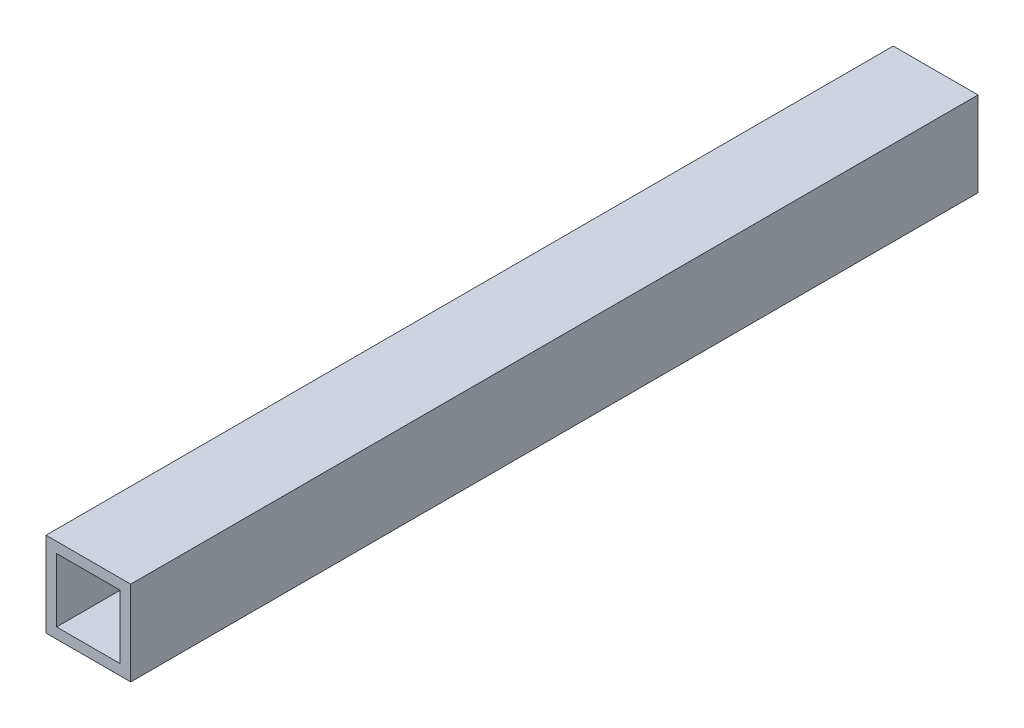
SolidWorks part; units mm, degrees
material "6061 Alloy"
ref_plane "Front Plane" through (0, 0, 0) normal (0, 0, 1) x (1, 0, 0)
ref_plane "Top Plane" through (0, 0, 0) normal (0, 1, 0) x (1, 0, 0)
ref_plane "Right Plane" through (0, 0, 0) normal (1, 0, 0) x (0, 0, -1)
sketch "Sketch1" plane through (0, 0, 0) normal (0, 0, 1) x (1, 0, 0)
  line L0 (12.7, 0) -> (9.525, 0) construction
  line L1 (-12.7, 0) -> (12.7, 0) construction
  line L2 (0, 12.7) -> (0, -12.7)
  point P7 (0, 0)
sketch "Sketch2" plane through (0, 0, 0) normal (1, 0, 0) x (0, 0, -1)
  line L0 (127, 0) -> (-127, 0)
  point P4 (0, 0)
  dimension "Length" = 254
sketch "Sketch3" plane through (0, 0, 0) normal (0, 0, 1) x (1, 0, 0)
  line L0 (-12.7, 0) -> (12.7, 0) construction
  line L5 (12.7, -12.7) -> (-12.7, -12.7)
  line L6 (12.7, -12.7) -> (12.7, 12.7)
  line L11 (12.7, 12.7) -> (-12.7, 12.7)
  line L12 (-12.7, -12.7) -> (-12.7, 12.7)
  line L14 (12.7, -12.7) -> (-12.7, 12.7) construction
  line L15 (12.7, 12.7) -> (-12.7, -12.7) construction
  line L16 (9.525, -9.525) -> (-9.525, -9.525)
  line L17 (9.525, -9.525) -> (9.525, 9.525)
  line L18 (9.525, 9.525) -> (-9.525, 9.525)
  line L19 (-9.525, -9.525) -> (-9.525, 9.525)
  line L20 (9.525, -9.525) -> (-9.525, 9.525) construction
  line L21 (9.525, 9.525) -> (-9.525, -9.525) construction
  point P0 (0, 0)
  point P5 (0, 0)
  point P13 (9.525, -12.7)
  dimension "D1" = 3.175
  dimension "D3" = 25.4
  dimension "D4" = 25.4
extrude "Boss-Extrude1" add sketch "Sketch3" along normal up to vertex (127 mm away) and the other way up to vertex (127 mm away) up to point (0, 0, 127) other way up to point (0, 0, -127)
sketch "Sketch5" plane through (0, 0, 0) normal (1, 0, 0) x (0, 0, -1)
  line L0 (-127, 0) -> (127, 0) construction
  line L3 (-127, -12.7) -> (-127, 12.7) construction
  line L4 (127, -12.7) -> (127, 12.7) construction
  point P6 (-98.425, 0)
  point P7 (-88.9, 0)
  point P8 (88.9, 0)
  point P10 (98.425, 0)
  dimension "D1" = 28.575
  dimension "D2" = 38.1
  dimension "D3" = 28.575
  dimension "D4" = 38.1
equation "\"D1@Sketch3\"=\"Wall thickness@Sketch1\""
equation "\"D1@Sketch5\"=\"Width@Sketch1\"*1.125"
equation "\"D2@Sketch5\"=\"Width@Sketch1\"*1.5"
equation "\"D3@Sketch5\"=\"D1@Sketch5\""
equation "\"D4@Sketch5\"=\"D2@Sketch5\""
equation "\"D2@Sketch3\"=\"Wall Thickness@Sketch1\""
